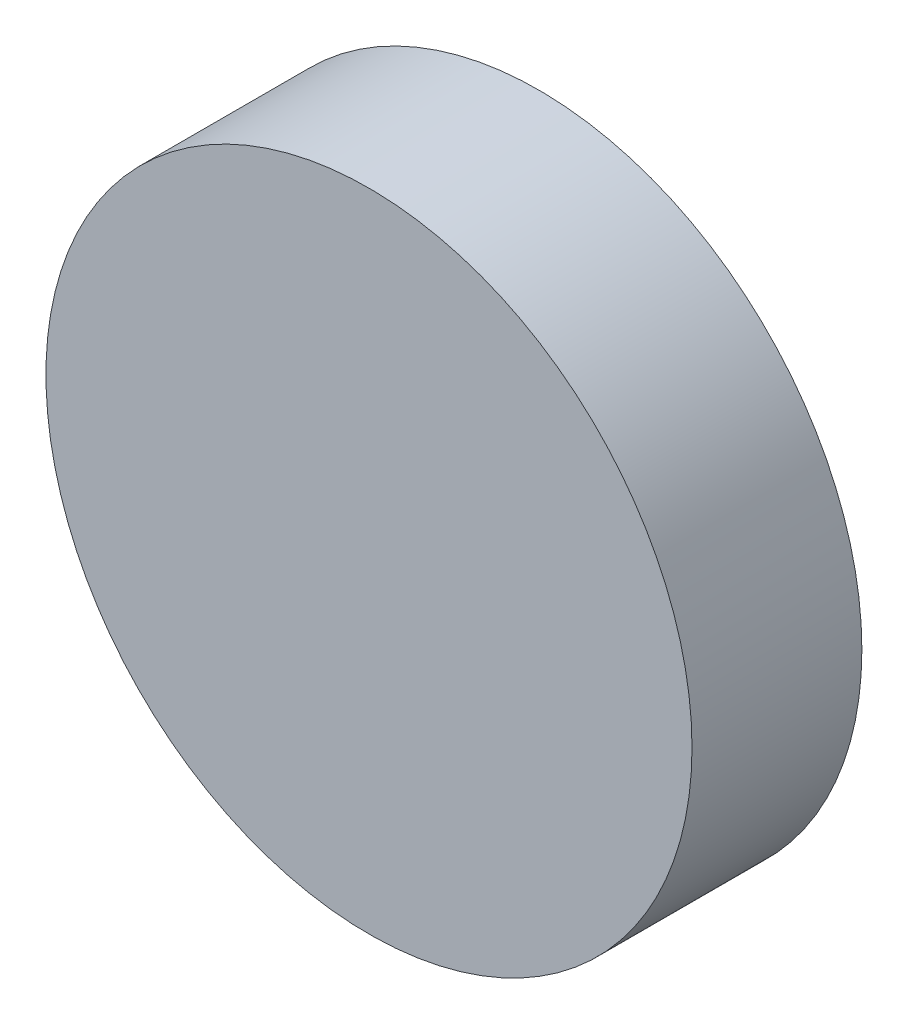
SolidWorks part; units mm, degrees
ref_plane "Спереди" through (0, 0, 0) normal (0, 0, 1) x (1, 0, 0)
ref_plane "Сверху" through (0, 0, 0) normal (0, 1, 0) x (1, 0, 0)
ref_plane "Справа" through (0, 0, 0) normal (1, 0, 0) x (0, 0, -1)
other "Configuration Table"
sketch "Маркировка" plane through (0, 0, 0) normal (0, 0, 1) x (1, 0, 0)
  text T0 "          ->Обозначение-00 МД [->Наименование]\r\n"
sketch "Эскиз1" plane through (0, 0, 0) normal (0, 0, 1) x (1, 0, 0)
  circle A0 centre (0, 0) radius 19.0174
extrude "Бобышка-Вытянуть1" add sketch "Эскиз1" along normal blind 10
